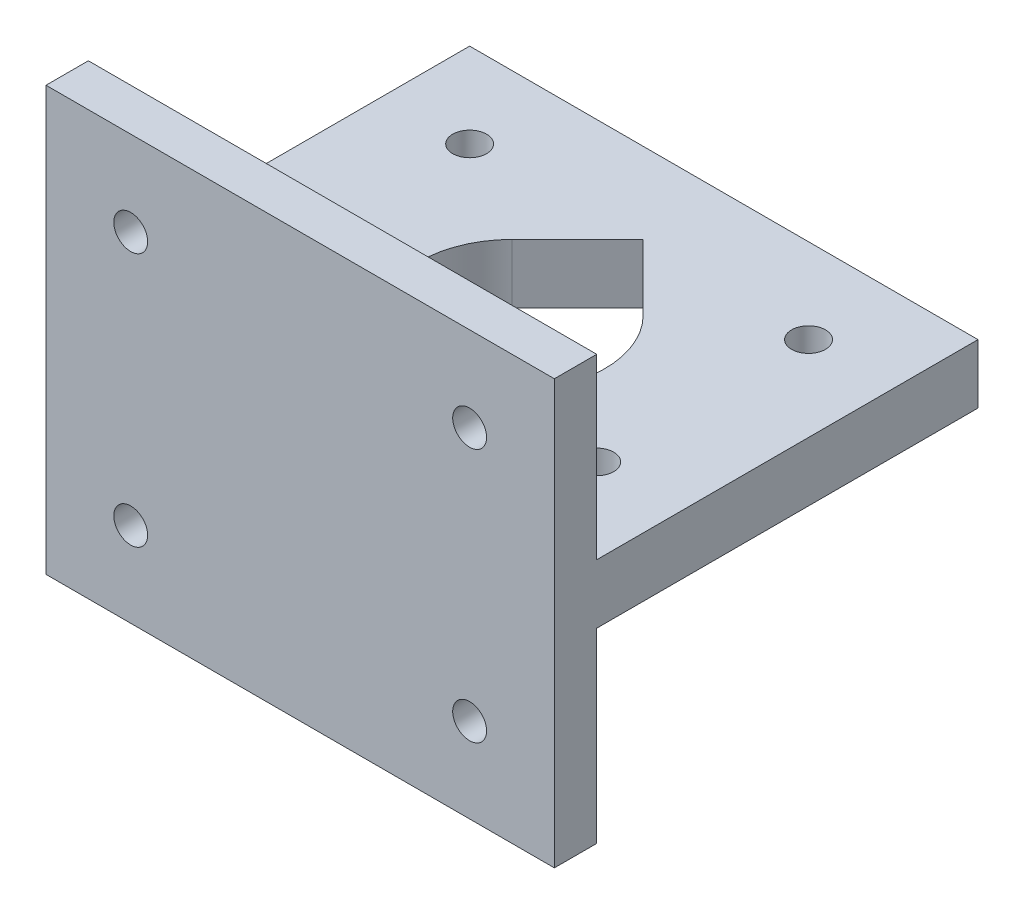
SolidWorks part; units mm, degrees
ref_plane "前视基准面" through (0, 0, 0) normal (0, 0, 1) x (1, 0, 0)
ref_plane "上视基准面" through (0, 0, 0) normal (0, 1, 0) x (1, 0, 0)
ref_plane "右视基准面" through (0, 0, 0) normal (1, 0, 0) x (0, 0, -1)
other "Configuration Table"
sketch "草图2" plane through (0, 0, 0) normal (0, 1, 0) x (1, 0, 0)
  line L1 (-30, -25) -> (30, -25)
  line L2 (-30, -25) -> (-30, 25)
  line L3 (-30, 25) -> (30, 25)
  line L4 (30, -25) -> (30, 25)
  line L5 (-30, -25) -> (30, 25) construction
  line L6 (-30, 25) -> (30, -25) construction
  circle A0 centre (0, 0) radius 10.85
  dimension "D1" = 21.7
  dimension "D2" = 50
  dimension "D3" = 60
extrude "凸台-拉伸1" add sketch "草图2" along normal blind 7
ref_plane "基准面1" through (0, 3, 0) normal (0, 1, 0) x (1, 0, 0)
sketch "草图4" plane through (0, 3, 0) normal (0, 1, 0) x (1, 0, 0)
  line L0 (30, -25) -> (30, 25) construction
  line L1 (-30, -25) -> (30, -25)
  line L2 (-30, -25) -> (-30, -20)
  line L3 (-30, -20) -> (30, -20)
  line L4 (30, -25) -> (30, -20)
  dimension "D1" = 5
extrude "凸台-拉伸2" add sketch "草图4" along normal mid plane 50
sketch "草图6" plane through (0, 0, 25) normal (0, 0, 1) x (1, 0, 0)
  line L0 (27.5, 3) -> (-27.5, 3) construction
  line L1 (-30, 28) -> (-20, 28)
  line L2 (-30, 28) -> (-30, 18)
  line L3 (-30, 18) -> (-20, 18)
  line L4 (-20, 28) -> (-20, 18)
  line L5 (0, -1000) -> (0, 49000) construction
  circle A0 centre (-20, 18) radius 2
  circle A1 centre (-20, -12) radius 2
  circle A2 centre (20, -12) radius 2
  circle A3 centre (20, 18) radius 2
  dimension "D3" = 4
  dimension "D1" = 10
  dimension "D2" = 10
extrude "切除-拉伸1" cut sketch "草图6" against normal blind 50 contours L3 A0 L4 | L4 A0 L3 | A3 | A1 | A2
sketch "草图8" plane through (0, 0, 0) normal (0, -1, 0) x (1, 0, 0)
  line L0 (0, -1000) -> (0, 49000) construction
  line L1 (-30, -25) -> (-20, -25)
  line L2 (-30, -25) -> (-30, -15)
  line L3 (-30, -15) -> (-20, -15)
  line L4 (-20, -25) -> (-20, -15)
  line L5 (-1000, 0) -> (49000, 0) construction
  line L7 (-30, 20) -> (-20, 20)
  line L8 (-30, 20) -> (-30, 10)
  line L9 (-30, 10) -> (-20, 10)
  line L10 (-20, 20) -> (-20, 10)
  circle A0 centre (-20, -15) radius 2
  circle A1 centre (20, -15) radius 2
  circle A2 centre (-20, 10) radius 2
  circle A3 centre (20, 10) radius 2
  dimension "D3" = 4
  dimension "D6" = 4
  dimension "D1" = 10
  dimension "D2" = 10
  dimension "D4" = 10
  dimension "D5" = 10
extrude "切除-拉伸4" cut sketch "草图8" against normal blind 50 contours L9 A2 L10 | L10 A2 L9 | A3 | A1 | A0
sketch "草图10" plane through (0, 7, 0) normal (0, 1, 0) x (1, 0, 0)
  circle A0 centre (0, 0) radius 10.95
  dimension "D1" = 21.9
extrude "切除-拉伸5" cut sketch "草图10" against normal blind 10
sketch "草图14" plane through (0, 7, 0) normal (0, 1, 0) x (1, 0, 0)
  line L0 (0, 0) -> (0, 15.4856)
  line L1 (0, 15.4856) -> (7.7428, 7.7428)
  line L2 (0, 15.4856) -> (-7.7428, 7.7428)
  circle A0 centre (0, 0) radius 10.95
  circle M3 centre (0, 0) radius 10.95
  dimension "D1" = 45
  dimension "D2" = 21.9
extrude "切除-拉伸12" cut sketch "草图14" against normal blind 10 contours L0 L2 M3 | L1 L0 M3 | A0
